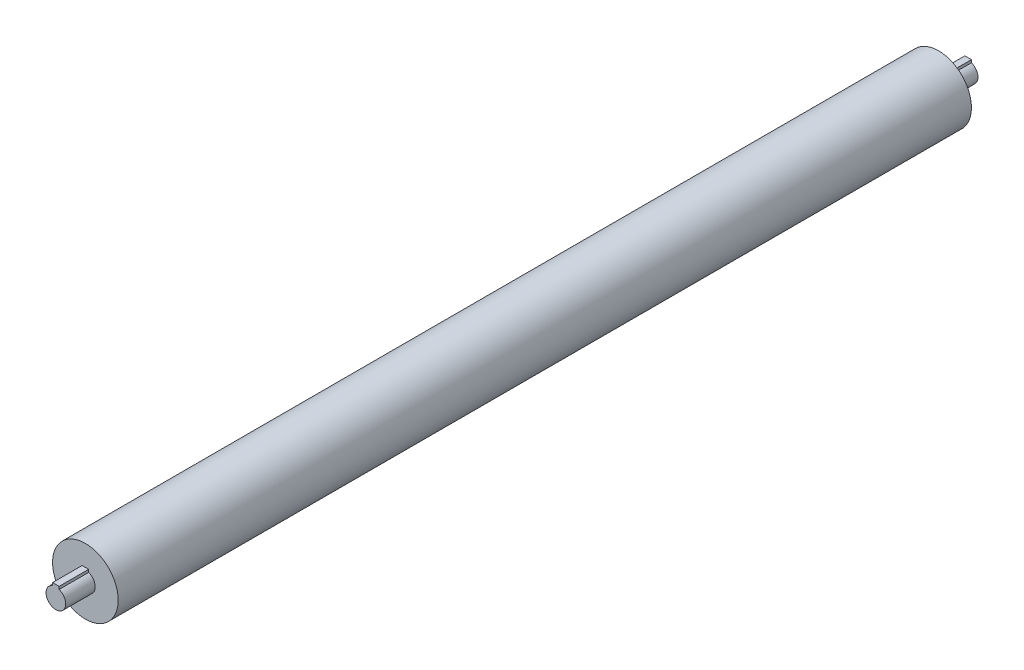
SolidWorks part; units mm, degrees
ref_plane "Front Plane" through (0, 0, 0) normal (0, 0, 1) x (1, 0, 0)
ref_plane "Top Plane" through (0, 0, 0) normal (0, 1, 0) x (1, 0, 0)
ref_plane "Right Plane" through (0, 0, 0) normal (1, 0, 0) x (0, 0, -1)
sketch "Sketch1" plane through (0, 0, 0) normal (0, 0, 1) x (1, 0, 0)
  circle A0 centre (0, 0) radius 50
  dimension "D1" = 100
extrude "Boss-Extrude1" add sketch "Sketch1" along normal mid plane 1300
sketch "Sketch4" plane through (0, 0, 0) normal (0, 0, 1) x (1, 0, 0)
  line L1 (-5, 14.1421) -> (-5, 18.3)
  line L4 (5, 18.3) -> (5, 14.1421)
  line L5 (-5, 18.3) -> (5, 18.3)
  arc A2 (-5, 14.1421) -> (5, 14.1421) centre (0, 0) ccw
  dimension "D2" = 10
  dimension "D1" = 15
  dimension "D3" = 18.3
  dimension "D4" = 5
extrude "Boss-Extrude2" add sketch "Sketch4" along normal mid plane 1390
sketch "Sketch5" [suppressed] plane through (0, 0, 0) normal (0, 0, 1) x (1, 0, 0)
  line L0 (7, 7.1414) -> (7, -7.1414) construction
  line L1 (-7, 7.1414) -> (-7, -7.1414) construction
  line L2 (7, 7.1414) -> (7, -7.1414)
  line L3 (-7, 7.1414) -> (-7, -7.1414)
  line L7 (-5, 18.3) -> (-5, 14.1421)
  line L8 (-5, 18.3) -> (-5, 14.1421)
  line L9 (5, 18.3) -> (-5, 18.3)
  line L10 (5, 18.3) -> (-5, 18.3)
  line L11 (5, 14.1421) -> (5, 18.3)
  line L12 (5, 14.1421) -> (5, 18.3)
  arc A1 (-5, 14.1421) -> (5, 14.1421) centre (0, 0) ccw
  arc A3 (-5, 14.1421) -> (5, 14.1421) centre (0, 0) ccw
  dimension "D1" = 0
extrude "Boss-Extrude3" [suppressed] add sketch "Sketch5" along normal mid plane 1210
